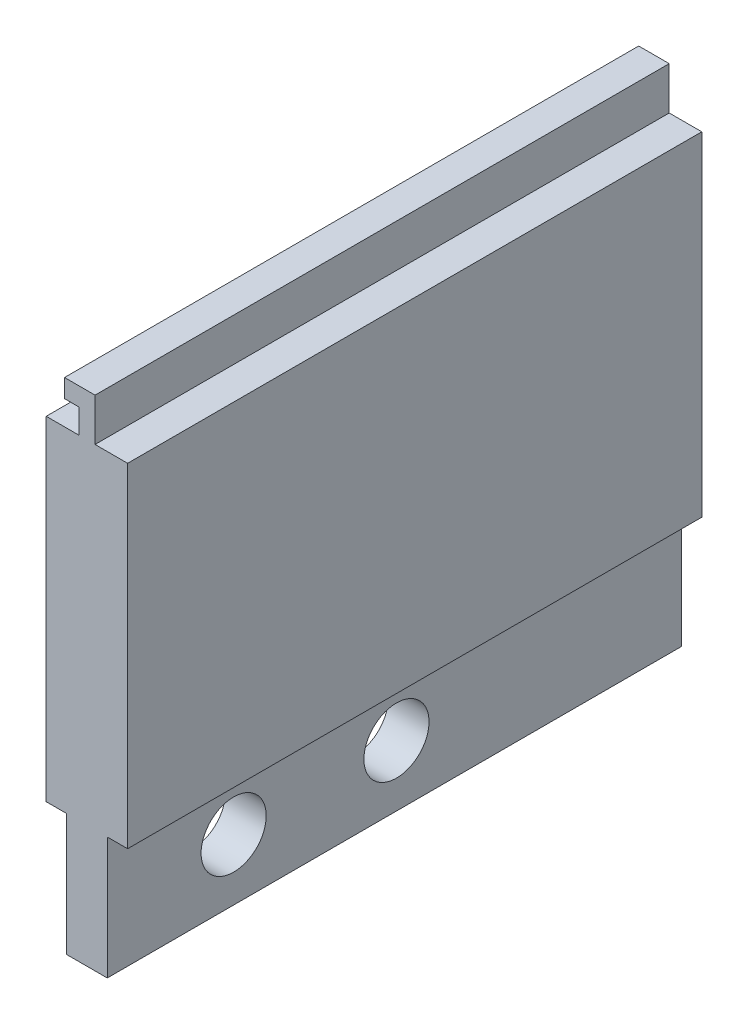
SolidWorks part; units mm, degrees
ref_plane "前视基准面" through (0, 0, 0) normal (0, 0, 1) x (1, 0, 0)
ref_plane "上视基准面" through (0, 0, 0) normal (0, 1, 0) x (1, 0, 0)
ref_plane "右视基准面" through (0, 0, 0) normal (1, 0, 0) x (0, 0, -1)
other "Configuration Table"
sketch "草图1" plane through (0, 0, 0) normal (0, 0, 1) x (1, 0, 0)
  line L1 (2.4, -8.3) -> (2.4, -6.2) construction
  line L2 (2.4, -6.2) -> (1.6, -6.2)
  line L3 (2.4, -6.2) -> (2.4, -8.3)
  line L4 (2.4, -8.3) -> (1.6, -8.3)
  line L5 (1.6, -6.2) -> (1.6, -8.3)
  line L6 (4, -8.3) -> (0, -8.3)
  line L7 (4, -8.3) -> (4, -24.7)
  line L8 (4, -24.7) -> (0, -24.7)
  line L9 (0, -8.3) -> (0, -24.7)
  line L10 (3, -24.7) -> (1, -24.7)
  line L11 (3, -24.7) -> (3, -30.7)
  line L12 (3, -30.7) -> (1, -30.7)
  line L13 (1, -24.7) -> (1, -30.7)
  line L18 (1.6, -8.3) -> (1.6, -6.2) construction
  line L21 (2.5, -6.2) -> (0.9, -6.2) construction
  line L23 (-0.1, -8.3) -> (1.6, -8.3) construction
  line L25 (0.9, -6.2) -> (0.9, -7.2) construction
  line L26 (1.6, -6.2) -> (0.9, -6.2)
  line L27 (1.6, -6.2) -> (1.6, -7.1)
  line L28 (1.6, -7.1) -> (0.9, -7.1)
  line L29 (0.9, -6.2) -> (0.9, -7.1)
  line L30 (0.9, -7.2) -> (1.5, -7.2) construction
  point P14 (2, -8.3)
  point P15 (2, -8.3)
  point P16 (2, -24.7)
  point P18 (2, -30.7)
  dimension "D1" = 2
  dimension "D2" = 4
  dimension "D3" = 16.4
  dimension "D4" = 6
  dimension "D5" = 0.1
extrude "凸台-拉伸1" add sketch "草图1" against normal blind 20 contours L2 L5 L4 L3 | L6 L9 L8 L7 L4 | L8 L13 L12 L11 | L26 L29 L28 L5
sketch "草图3" plane through (3, 0, 0) normal (1, 0, 0) x (0, 0, -1)
  circle A0 centre (6.2085, -27.7) radius 1.6
  circle A1 centre (14.2085, -27.7) radius 1.6
  dimension "D1" = 3.2
  dimension "D2" = 3.2
extrude "切除-拉伸1" cut sketch "草图3" against normal through all
sketch "草图4" plane through (0, 0, -20) normal (0, 0, -1) x (-1, 0, 0)
  line L14 (-0.9, -6.2) -> (-2.4, -6.2)
  line L15 (-2.4, -6.2) -> (-2.4, -8.3)
  line L16 (-2.4, -8.3) -> (-4, -8.3)
  line L17 (-4, -8.3) -> (-4, -24.7)
  line L18 (-4, -24.7) -> (-3, -24.7)
  line L19 (-3, -24.7) -> (-3, -30.7)
  line L20 (-3, -30.7) -> (-1, -30.7)
  line L21 (-1, -30.7) -> (-1, -24.7)
  line L22 (-1, -24.7) -> (0, -24.7)
  line L23 (0, -24.7) -> (0, -8.3)
  line L24 (0, -8.3) -> (-1.6, -8.3)
  line L25 (-1.6, -8.3) -> (-1.6, -7.1)
  line L26 (-1.6, -7.1) -> (-0.9, -7.1)
  line L27 (-0.9, -7.1) -> (-0.9, -6.2)
  line L28 (-0.9, -6.2) -> (-2.4, -6.2)
  line L29 (-2.4, -6.2) -> (-2.4, -8.3)
  line L30 (-2.4, -8.3) -> (-4, -8.3)
  line L31 (-4, -8.3) -> (-4, -24.7)
  line L32 (-4, -24.7) -> (-3, -24.7)
  line L33 (-3, -24.7) -> (-3, -30.7)
  line L34 (-3, -30.7) -> (-1, -30.7)
  line L35 (-1, -30.7) -> (-1, -24.7)
  line L36 (-1, -24.7) -> (0, -24.7)
  line L37 (0, -24.7) -> (0, -8.3)
  line L38 (0, -8.3) -> (-1.6, -8.3)
  line L39 (-1.6, -8.3) -> (-1.6, -7.1)
  line L40 (-1.6, -7.1) -> (-0.9, -7.1)
  line L41 (-0.9, -7.1) -> (-0.9, -6.2)
  dimension "D1" = 0
extrude "凸台-拉伸2" add sketch "草图4" along normal up to surface (8.2085 mm away)
